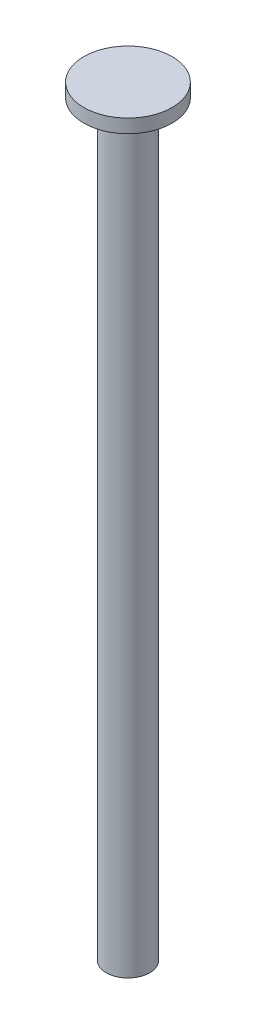
SolidWorks part; units mm, degrees
ref_plane "Front Plane" through (0, 0, 0) normal (0, 0, 1) x (1, 0, 0)
ref_plane "Top Plane" through (0, 0, 0) normal (0, 1, 0) x (1, 0, 0)
ref_plane "Right Plane" through (0, 0, 0) normal (1, 0, 0) x (0, 0, -1)
sketch "Sketch1" plane through (0, 0, 0) normal (0, 1, 0) x (1, 0, 0)
  circle A0 centre (0, 0) radius 3.25
  dimension "D1" = 6.5
extrude "Boss-Extrude1" add sketch "Sketch1" along normal blind 1 contours A0
sketch "Sketch2" plane through (0, 0, 0) normal (0, 1, 0) x (1, 0, 0)
  circle A0 centre (0, 0) radius 1.6
  dimension "D1" = 3.2
extrude "Boss-Extrude2" add sketch "Sketch2" against normal blind 55
